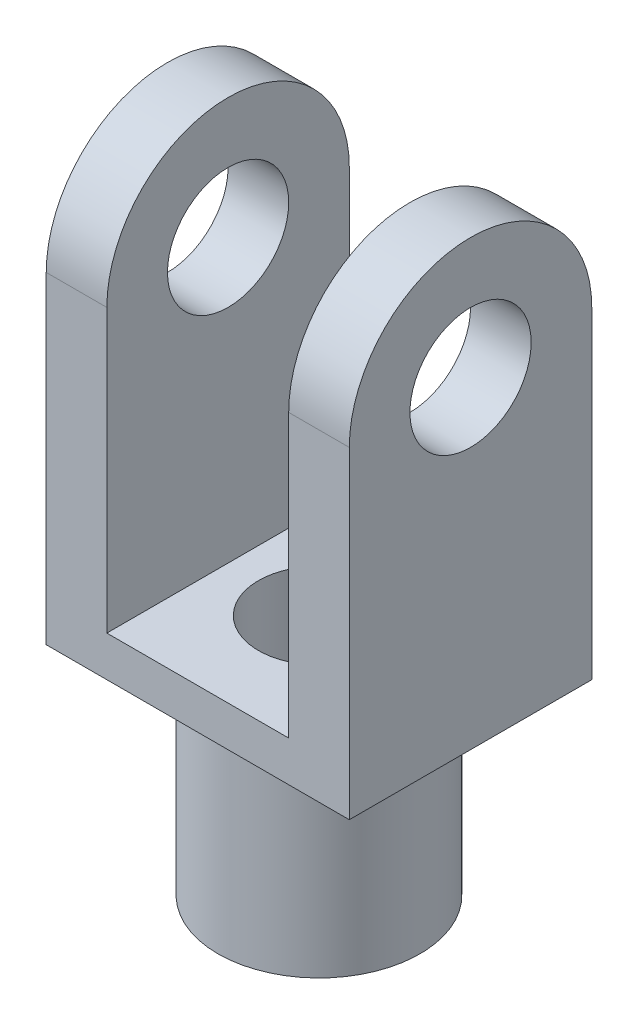
SolidWorks part; units mm, degrees
ref_plane "前视基准面" through (0, 0, 0) normal (0, 0, 1) x (1, 0, 0)
ref_plane "上视基准面" through (0, 0, 0) normal (0, 1, 0) x (1, 0, 0)
ref_plane "右视基准面" through (0, 0, 0) normal (1, 0, 0) x (0, 0, -1)
other "Configuration Table"
sketch "草图1" plane through (0, 0, 0) normal (0, 1, 0) x (1, 0, 0)
  circle A0 centre (0, 0) radius 5
  dimension "D1" = 10
extrude "凸台-拉伸1" add sketch "草图1" along normal blind 10
sketch "草图2" plane through (0, 10, 0) normal (0, 1, 0) x (1, 0, 0)
  line L1 (-7.5, -6) -> (7.5, -6)
  line L2 (-7.5, -6) -> (-7.5, 6)
  line L3 (-7.5, 6) -> (7.5, 6)
  line L4 (7.5, -6) -> (7.5, 6)
  line L5 (-7.5, -6) -> (7.5, 6) construction
  line L6 (-7.5, 6) -> (7.5, -6) construction
  point P0 (0, 0)
  dimension "D1" = 12
  dimension "D2" = 15
extrude "凸台-拉伸2" add sketch "草图2" along normal blind 2
sketch "草图4" plane through (0, 0, 0) normal (0, -1, 0) x (-1, 0, 0)
  circle A0 centre (0, 0) radius 3
  dimension "D1" = 6
extrude "切除-拉伸1" cut sketch "草图4" against normal through all
sketch "草图5" plane through (0, 12, 0) normal (0, 1, 0) x (1, 0, 0)
  line L1 (-4.5, -6) -> (4.5, -6)
  line L2 (-4.5, -6) -> (-4.5, 6)
  line L3 (-4.5, 6) -> (4.5, 6)
  line L4 (7.5, -6) -> (7.5, 6)
  line L5 (7.5, 6) -> (-7.5, 6)
  line L6 (-7.5, 6) -> (-7.5, -6)
  line L7 (-7.5, -6) -> (7.5, -6)
  line L8 (7.5, -6) -> (7.5, 6)
  line L9 (7.5, 6) -> (-7.5, 6)
  line L10 (-7.5, 6) -> (-7.5, -6)
  line L11 (-7.5, -6) -> (7.5, -6)
  line L12 (4.5, -6) -> (4.5, 6)
  line L13 (-4.5, -6) -> (4.5, 6) construction
  line L14 (-4.5, 6) -> (4.5, -6) construction
  point P2 (0, 0)
  line M10 (7.5, -6) -> (7.5, 6)
  line M11 (7.5, 6) -> (-7.5, 6)
  line M12 (-7.5, 6) -> (-7.5, -6)
  line M13 (-7.5, -6) -> (7.5, -6)
  dimension "D2" = 3
  dimension "D1" = 0
extrude "凸台-拉伸3" add sketch "草图5" along normal blind 20 contours L2 M13 M11 M12 | L12 M13 M10 M11
sketch "草图6" plane through (-7.5, 0, 0) normal (-1, 0, 0) x (0, 0, 1)
  line L0 (0, -1.6263) -> (0, 25.9578) construction
  line L1 (-6, -1.6263) -> (-6, 25.9578)
  line L2 (6, -1.6263) -> (6, 25.9578)
  line L3 (-6, 32) -> (-6, 10) construction
  line L4 (-6, 10) -> (6, 10) construction
  line L5 (-6, 10) -> (6, 10)
  arc A0 (-6, -1.6263) -> (6, -1.6263) centre (0, -1.6263) ccw
  arc A1 (6, 25.9578) -> (-6, 25.9578) centre (0, 25.9578) ccw
  point P3 (0, 12.1658)
  point P12 (0, 0)
  point P13 (0, -1.6263)
extrude "切除-拉伸2" cut sketch "草图6" against normal through all flip side to cut
sketch "草图7" plane through (7.5, 0, 0) normal (1, 0, 0) x (0, 0, -1)
  circle A0 centre (0, 25.9578) radius 3
  dimension "D1" = 6
extrude "切除-拉伸3" cut sketch "草图7" against normal through all
